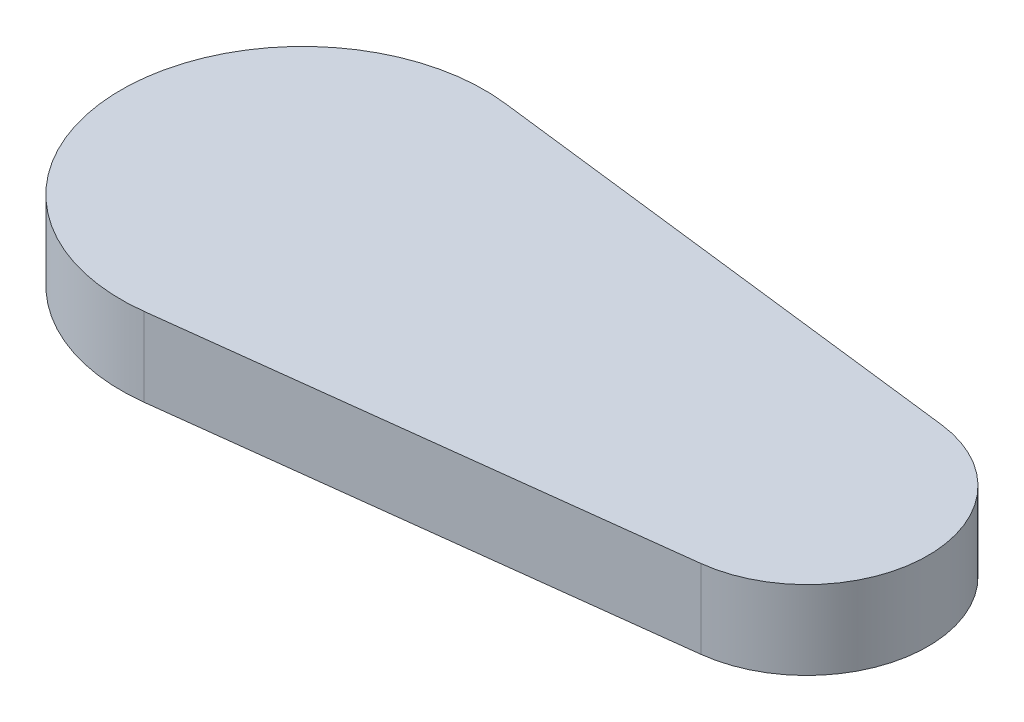
SolidWorks part; units mm, degrees
ref_plane "Płaszczyzna przednia" through (0, 0, 0) normal (0, 0, 1) x (1, 0, 0)
ref_plane "Płaszczyzna górna" through (0, 0, 0) normal (0, 1, 0) x (1, 0, 0)
ref_plane "Płaszczyzna prawa" through (0, 0, 0) normal (1, 0, 0) x (0, 0, -1)
sketch "Sketch1" plane through (0, 0, 0) normal (0, 1, 0) x (1, 0, 0)
  line L0 (0.7207, 5.9566) -> (17.1305, 3.971)
  line L1 (0.7207, -5.9566) -> (17.1305, -3.971)
  circle A0 centre (0, 0) radius 6
  circle A1 centre (16.65, 0) radius 4
  point P9 (0, 0)
  point P10 (10.2234, 0)
  dimension "D1" = 8
  dimension "D2" = 12
  dimension "D3" = 16.65
extrude "Boss-Extrude1" add sketch "Sketch1" along normal blind 2.6 contours A0 | A1 | A1 L0 A0 L1
